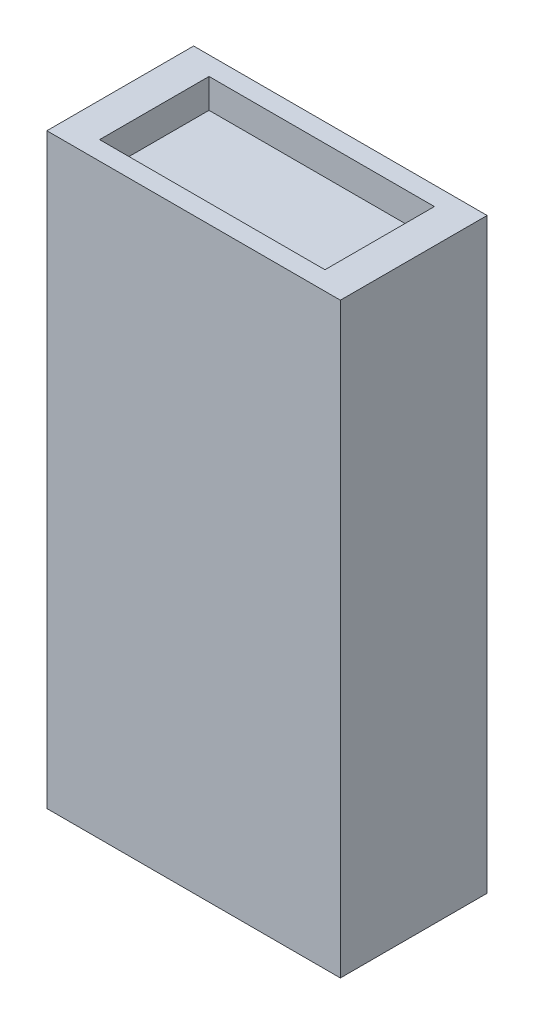
SolidWorks part; units mm, degrees
ref_plane "前视基准面" through (0, 0, 0) normal (0, 0, 1) x (1, 0, 0)
ref_plane "上视基准面" through (0, 0, 0) normal (0, 1, 0) x (1, 0, 0)
ref_plane "右视基准面" through (0, 0, 0) normal (1, 0, 0) x (0, 0, -1)
sketch "草图1" plane through (0, 0, 0) normal (0, 0, 1) x (1, 0, 0)
  line L1 (-10, 20) -> (10, 20)
  line L2 (-10, 20) -> (-10, -20)
  line L3 (-10, -20) -> (10, -20)
  line L4 (10, 20) -> (10, -20)
  line L5 (-10, 20) -> (10, -20) construction
  line L6 (-10, -20) -> (10, 20) construction
  point P0 (0, 0)
  dimension "D1" = 20
  dimension "D2" = 40
extrude "凸台-拉伸1" add sketch "草图1" along normal blind 10
sketch "草图2" plane through (0, 20, 0) normal (0, 1, 0) x (1, 0, 0)
  line L8 (-7.6785, -8.7282) -> (7.6785, -8.7282)
  line L13 (-7.6785, -8.7282) -> (-7.6785, -1.2718)
  line L14 (-7.6785, -1.2718) -> (7.6785, -1.2718)
  line L15 (7.6785, -8.7282) -> (7.6785, -1.2718)
  line L16 (-7.6785, -8.7282) -> (7.6785, -1.2718) construction
  line L17 (-7.6785, -1.2718) -> (7.6785, -8.7282) construction
  point P5 (0, -2.5)
  point P6 (-1.9697, -5)
  point P8 (0, -5)
extrude "切除-拉伸1" cut sketch "草图2" against normal blind 2
